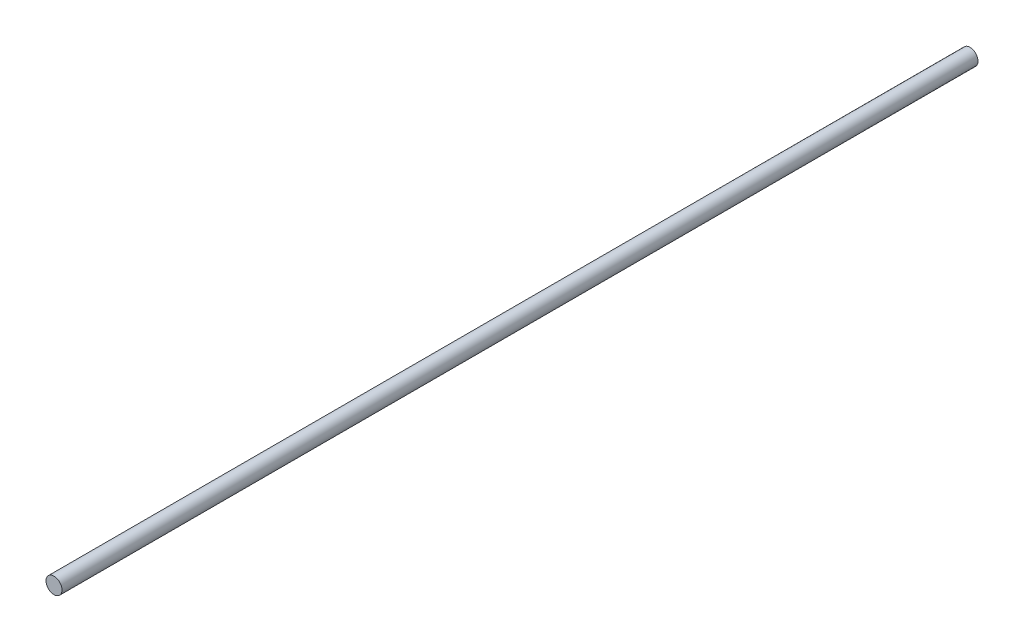
SolidWorks part; units mm, degrees
ref_plane "Front Plane" through (0, 0, 0) normal (0, 0, 1) x (1, 0, 0)
ref_plane "Top Plane" through (0, 0, 0) normal (0, 1, 0) x (1, 0, 0)
ref_plane "Right Plane" through (0, 0, 0) normal (1, 0, 0) x (0, 0, -1)
sketch "Sketch1" plane through (0, 0, 0) normal (0, 0, 1) x (1, 0, 0)
  circle A0 centre (0, 0) radius 0.875
  dimension "D1" = 1.75
extrude "Boss-Extrude1" add sketch "Sketch1" along normal blind 100
